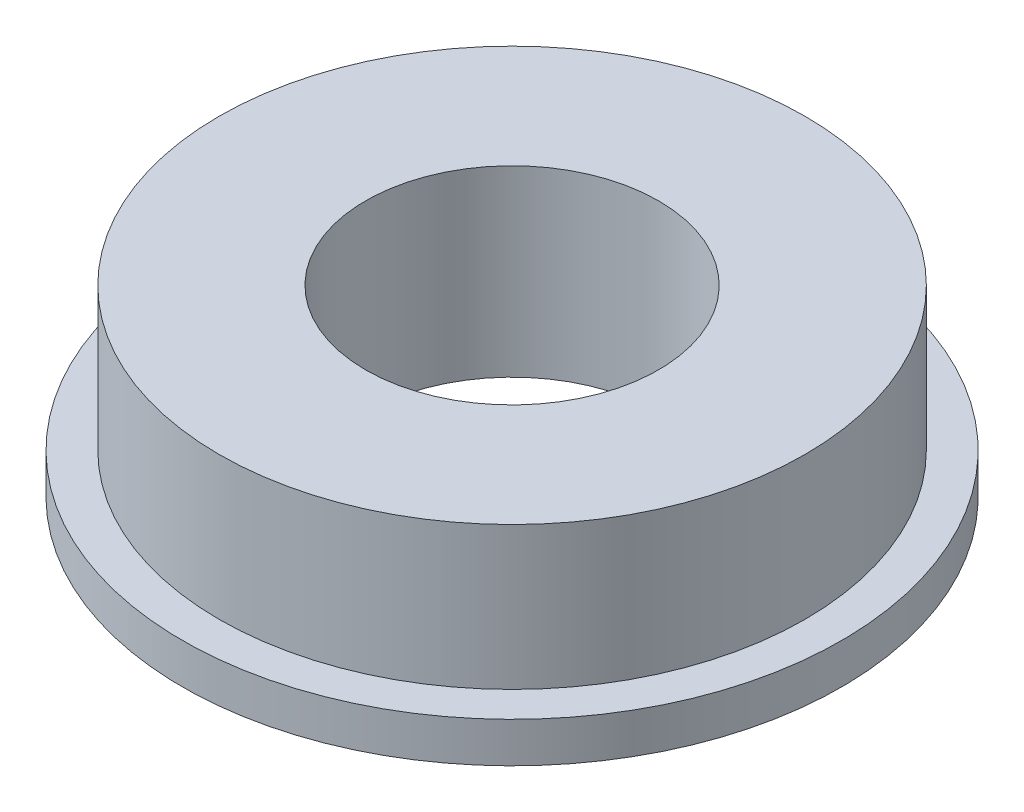
SolidWorks part; units mm, degrees
ref_plane "前视基准面" through (0, 0, 0) normal (0, 0, 1) x (1, 0, 0)
ref_plane "上视基准面" through (0, 0, 0) normal (0, 1, 0) x (1, 0, 0)
ref_plane "右视基准面" through (0, 0, 0) normal (1, 0, 0) x (0, 0, -1)
sketch "草图1" plane through (0, 0, 0) normal (0, 1, 0) x (1, 0, 0)
  circle A0 centre (0, 0) radius 4
  circle A1 centre (0, 0) radius 8
  dimension "D1" = 8
  dimension "D2" = 16
extrude "凸台-拉伸1" add sketch "草图1" along normal blind 3.9
sketch "草图2" plane through (0, 0, 0) normal (0, -1, 0) x (1, 0, 0)
  circle A0 centre (0, 0) radius 4 construction
  circle A1 centre (0, 0) radius 4
  circle A2 centre (0, 0) radius 9
  dimension "D1" = 18
extrude "凸台-拉伸2" add sketch "草图2" along normal blind 1.1
